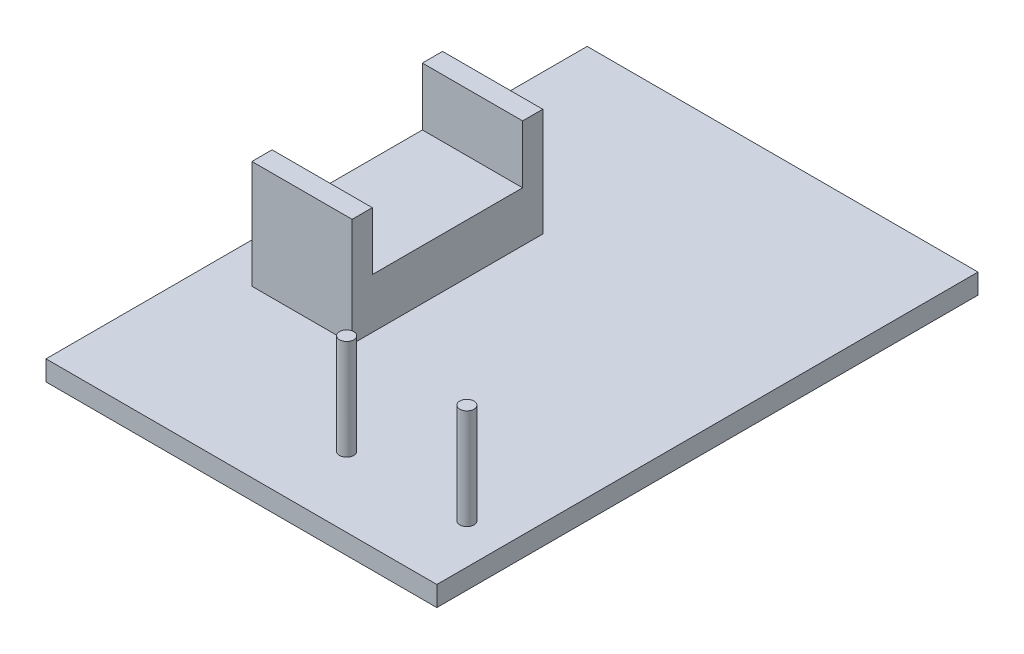
SolidWorks part; units mm, degrees
ref_plane "Front Plane" through (0, 0, 0) normal (0, 0, 1) x (1, 0, 0)
ref_plane "Top Plane" through (0, 0, 0) normal (0, 1, 0) x (1, 0, 0)
ref_plane "Right Plane" through (0, 0, 0) normal (1, 0, 0) x (0, 0, -1)
sketch "Sketch1" plane through (0, 0, 0) normal (0, 1, 0) x (1, 0, 0)
  line L1 (-24.765, -34.29) -> (24.765, -34.29)
  line L2 (-24.765, -34.29) -> (-24.765, 34.29)
  line L3 (-24.765, 34.29) -> (24.765, 34.29)
  line L4 (24.765, -34.29) -> (24.765, 34.29)
  line L5 (-24.765, -34.29) -> (24.765, 34.29) construction
  line L6 (-24.765, 34.29) -> (24.765, -34.29) construction
  point P0 (0, 0)
  point P6 (26.0656, 51.8065)
  point P8 (-23.4644, -16.7735)
  point P10 (0, 0)
  dimension "D1" = 68.58
  dimension "D2" = 49.53
extrude "Boss-Extrude1" add sketch "Sketch1" along normal blind 2.54
sketch "Sketch3" plane through (0, 2.54, 0) normal (0, 1, 0) x (1, 0, 0)
  line L0 (4.445, -25.4) -> (19.685, -25.4) construction
  line L1 (4.445, -25.4) -> (4.445, 15.24) construction
  line L2 (4.445, 15.24) -> (19.685, 15.24) construction
  line L3 (24.765, -34.29) -> (24.765, 34.29) construction
  line L4 (-24.765, -34.29) -> (24.765, -34.29) construction
  circle A0 centre (4.445, -25.4) radius 0.9
  circle A1 centre (19.685, -25.4) radius 0.9
  circle A2 centre (4.445, 15.24) radius 0.9 construction
  circle A3 centre (19.685, 15.24) radius 0.9 construction
  point P8 (5.7642, -31.3695)
  dimension "D1" = 1.8
  dimension "D2" = 40.64
  dimension "D3" = 15.24
  dimension "D4" = 5.08
  dimension "D5" = 8.89
extrude "Boss-Extrude3" add sketch "Sketch3" along normal blind 12.7
sketch "Sketch4" plane through (-24.765, 0, 0) normal (-1, 0, 0) x (0, 0, 1)
  line L0 (-10.883, 2.54) -> (-10.883, 16.2343)
  line L1 (-34.29, 2.54) -> (34.29, 2.54) construction
  line L2 (-10.883, 16.2343) -> (-8.3278, 16.2343)
  line L3 (-8.3278, 16.2343) -> (-8.3278, 8.89)
  line L4 (-8.3278, 8.89) -> (10.7222, 8.89)
  line L5 (10.7222, 8.89) -> (10.7222, 16.2343)
  line L6 (10.7222, 16.2343) -> (13.2773, 16.2343)
  line L7 (13.2773, 16.2343) -> (13.2773, 2.54)
  line L9 (13.2773, 2.54) -> (-10.883, 2.54)
  point P11 (3.5236, 2.54)
  dimension "D1" = 19.05
  dimension "D2" = 6.35
extrude "Boss-Extrude4" add sketch "Sketch4" against normal blind 12.7 from offset 5.08
